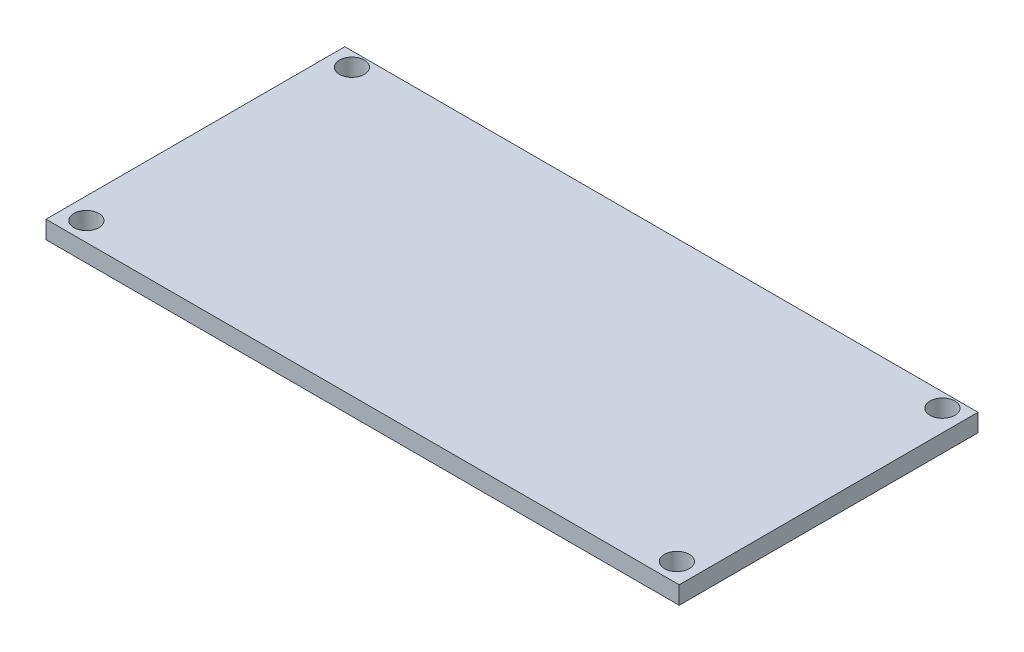
SolidWorks part; units mm, degrees
ref_plane "Front Plane" through (0, 0, 0) normal (0, 0, 1) x (1, 0, 0)
ref_plane "Top Plane" through (0, 0, 0) normal (0, 1, 0) x (1, 0, 0)
ref_plane "Right Plane" through (0, 0, 0) normal (1, 0, 0) x (0, 0, -1)
sketch "Sketch1" plane through (0, 0, 0) normal (0, 1, 0) x (1, 0, 0)
  line L1 (0, 42) -> (89, 42)
  line L2 (0, 42) -> (0, 0)
  line L3 (0, 0) -> (89, 0)
  line L4 (89, 42) -> (89, 0)
  dimension "D1" = 89
  dimension "D2" = 42
extrude "Boss-Extrude1" add sketch "Sketch1" along normal blind 2.5
sketch "Sketch2" plane through (0, 2.5, 0) normal (0, 1, 0) x (1, 0, 0)
  line L0 (188.911, 855.9926) -> (712.911, 855.9926) construction
  line L1 (-682.1085, 125.151) -> (-682.1085, 625.151) construction
  line L2 (-711.1265, 125.094) -> (-711.1265, 625.094) construction
sketch "Sketch3" plane through (0, 2.5, 0) normal (0, 1, 0) x (1, 0, 0)
  line L0 (44.5, 56.0805) -> (44.5, -2.5292) construction
  line L1 (89, 42) -> (0, 42) construction
  line L2 (-7.72, 21.3373) -> (93.6913, 21.3373) construction
  line L4 (0, 42) -> (0, 0) construction
  circle A0 centre (3, 40) radius 1.75
  circle A1 centre (86, 40) radius 1.75
  circle A2 centre (86, 2.6746) radius 1.75
  circle A3 centre (3, 2.6746) radius 1.75
  point P6 (44.5, 42)
  dimension "D1" = 3.5
  dimension "D2" = 2
  dimension "D3" = 3
extrude "Cut-Extrude1" cut sketch "Sketch3" against normal through all
ref_plane "Plane1" through (0, 0, -7) normal (0, 0, 1) x (1, 0, 0)
sketch "Sketch5" plane through (0, 0, -7) normal (0, 0, 1) x (1, 0, 0)
  line L0 (11.1829, 0) -> (11.1829, -18.0943)
  line L1 (11.1829, -18.0943) -> (12.8656, -18.0943)
  line L2 (12.8656, -18.0943) -> (12.8656, -9.0472)
  line L3 (12.8656, -9.0472) -> (14.5472, -7.3656)
  line L4 (14.5472, -7.3656) -> (23.9718, -7.3656)
  line L5 (23.9718, -7.3656) -> (26.9166, -4.9268)
  line L6 (26.9166, -4.9268) -> (37.8124, -4.9268)
  line L7 (37.8124, -4.9268) -> (38.9903, -2.8234)
  line L8 (38.9903, -2.8234) -> (48.3295, -2.8234)
  line L9 (44.5, 20.5552) -> (44.5, -28.8034) construction
  line L10 (0, 0) -> (89, 0) construction
  point P14 (44.5, 0)
